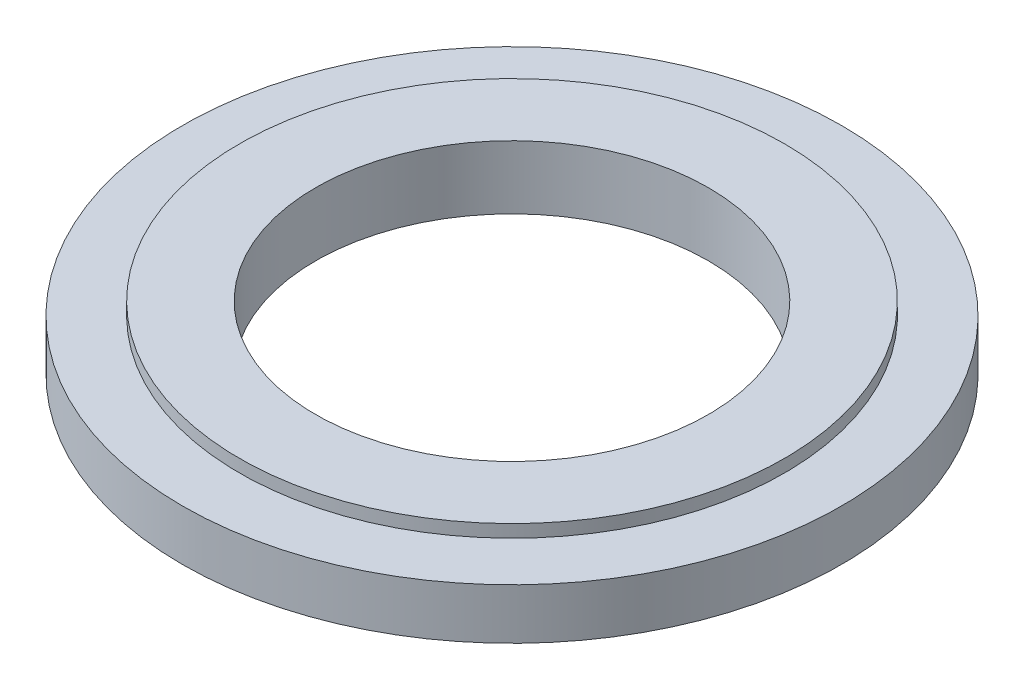
SolidWorks part; units mm, degrees
material "ABS"
ref_plane "Front Plane" through (0, 0, 0) normal (0, 0, 1) x (1, 0, 0)
ref_plane "Top Plane" through (0, 0, 0) normal (0, 1, 0) x (1, 0, 0)
ref_plane "Right Plane" through (0, 0, 0) normal (1, 0, 0) x (0, 0, -1)
sketch "Sketch1" plane through (0, 0, 0) normal (0, 0, 1) x (1, 0, 0)
  line L0 (0, 0) -> (0, 23.0273) construction
  line L1 (-7.75, 0) -> (-13, 0)
  line L2 (-13, 0) -> (-13, 2)
  line L3 (-13, 2) -> (-10.75, 2)
  line L4 (-10.75, 2) -> (-10.75, 2.5)
  line L5 (-10.75, 2.5) -> (-7.75, 2.5)
  line L6 (-7.75, 2.5) -> (-7.75, 0)
  dimension "D1" = 15.5
  dimension "D2" = 3
  dimension "D3" = 0.5
  dimension "D4" = 2
  dimension "D5" = 26
revolve "Revolve1" add sketch "Sketch1" angle 360 about L0
sketch "Sketch2" [suppressed] plane through (0, 3.5, 0) normal (0, 1, 0) x (1, 0, 0)
  circle A0 centre (0, 0) radius 8.7 construction
  circle A1 centre (0, 0) radius 9.7
  circle A2 centre (0, 0) radius 9.7
  circle A3 centre (0, 0) radius 8.7
  dimension "D1" = 0
extrude "Cut-Extrude1" [suppressed] cut sketch "Sketch2" against normal up to surface (0.5 mm away)
